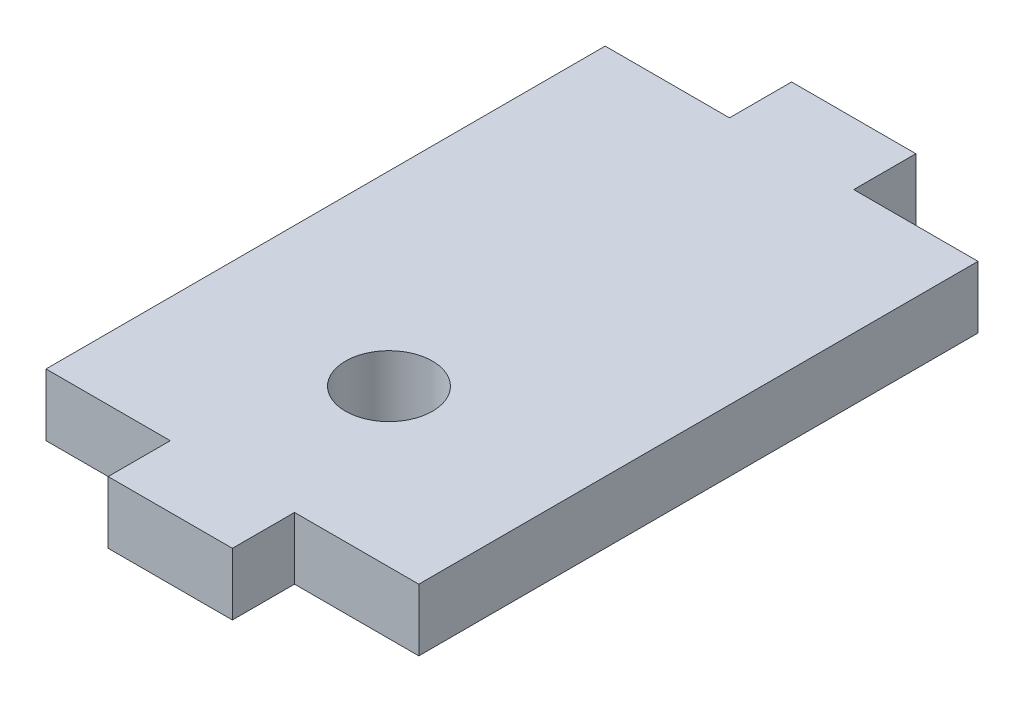
SolidWorks part; units mm, degrees
ref_plane "Front Plane" through (0, 0, 0) normal (0, 0, 1) x (1, 0, 0)
ref_plane "Top Plane" through (0, 0, 0) normal (0, 1, 0) x (1, 0, 0)
ref_plane "Right Plane" through (0, 0, 0) normal (1, 0, 0) x (0, 0, -1)
sketch "Sketch1" plane through (0, 0, 0) normal (0, 1, 0) x (1, 0, 0)
  line L0 (0, 0) -> (-15, 0) construction
  line L1 (15, 22.5) -> (-15, 22.5)
  line L2 (15, 22.5) -> (15, -22.5)
  line L3 (15, -22.5) -> (-15, -22.5)
  line L4 (-15, 22.5) -> (-15, -22.5)
  line L5 (15, 22.5) -> (-15, -22.5) construction
  line L6 (15, -22.5) -> (-15, 22.5) construction
  line L7 (-5, -22.5) -> (5, -22.5)
  line L8 (-5, -22.5) -> (-5, -27.5)
  line L9 (-5, -27.5) -> (5, -27.5)
  line L10 (5, -22.5) -> (5, -27.5)
  line L12 (5, 27.5) -> (-5, 27.5)
  line L13 (5, 27.5) -> (5, 22.5)
  line L14 (5, 22.5) -> (-5, 22.5)
  line L15 (-5, 27.5) -> (-5, 22.5)
  circle A2 centre (0, -9.9) radius 3.5
  point P0 (0, 0)
  point P11 (0, -27.5)
  point P21 (0, 22.5)
  point P22 (0, 22.5)
  dimension "D7" = 7
  dimension "D1" = 30
  dimension "D2" = 45
  dimension "D3" = 5
  dimension "D4" = 10
  dimension "D6" = 12.6
  dimension "D5" = 10
  dimension "D8" = 5
extrude "Boss-Extrude1" add sketch "Sketch1" along normal blind 5
equation "\"body\"=0.8"
equation "\"thick5mm\" = 5mm"
equation "\"D1@Boss-Extrude1\" = \"thick5mm\""
equation "\"D5@Sketch1\"=\"D4@Sketch1\""
equation "\"D8@Sketch1\"= \"thick5mm\""
equation "\"D3@Sketch1\"=\"thick5mm\""
